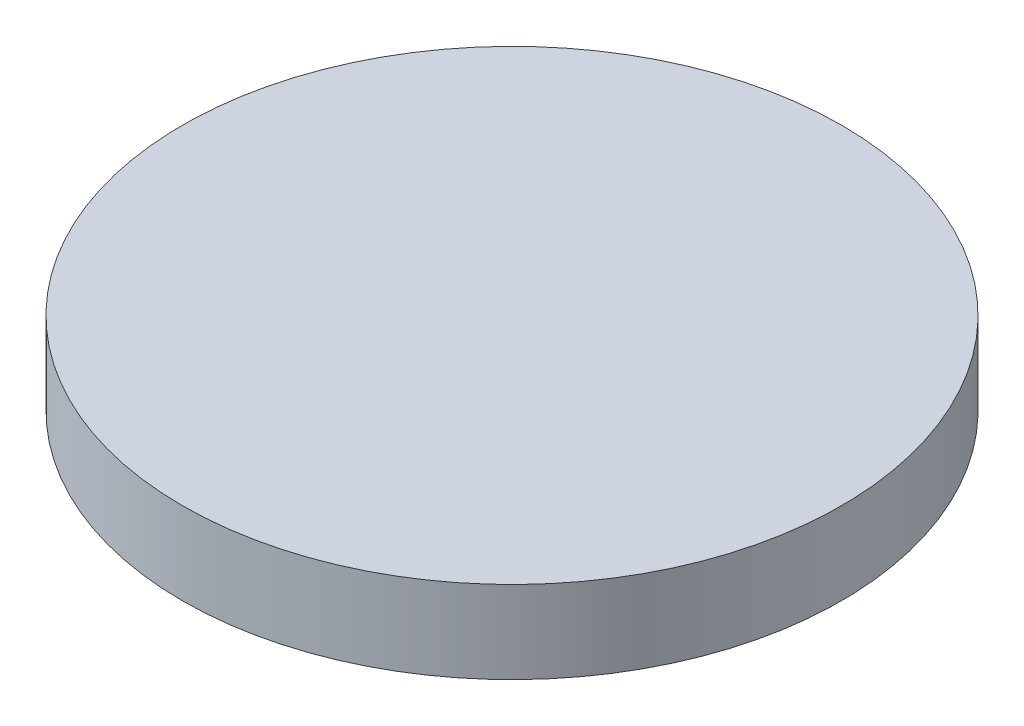
SolidWorks part; units mm, degrees
material "NeFeB Magnet"
ref_plane "Front Plane" through (0, 0, 0) normal (0, 0, 1) x (1, 0, 0)
ref_plane "Top Plane" through (0, 0, 0) normal (0, 1, 0) x (1, 0, 0)
ref_plane "Right Plane" through (0, 0, 0) normal (1, 0, 0) x (0, 0, -1)
sketch "Sketch1" plane through (0, 0, 0) normal (0, 1, 0) x (1, 0, 0)
  circle A0 centre (0, 0) radius 4
  dimension "D1" = 8
extrude "Boss-Extrude1" add sketch "Sketch1" along normal blind 1
